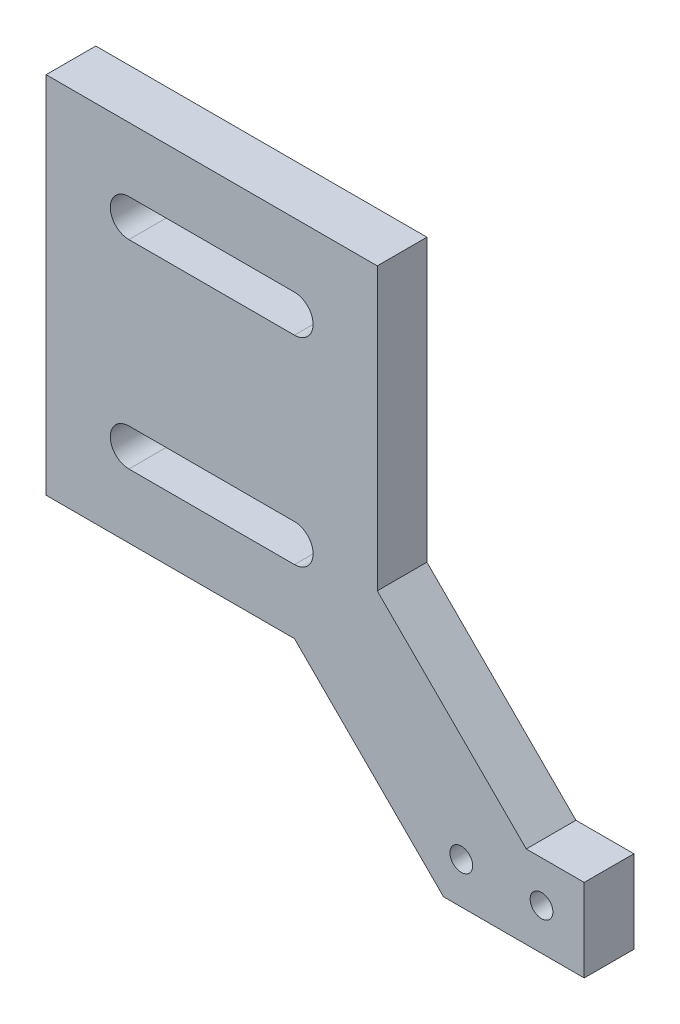
SolidWorks part; units mm, degrees
ref_plane "Front Plane" through (0, 0, 0) normal (0, 0, 1) x (1, 0, 0)
ref_plane "Top Plane" through (0, 0, 0) normal (0, 1, 0) x (1, 0, 0)
ref_plane "Right Plane" through (0, 0, 0) normal (1, 0, 0) x (0, 0, -1)
sketch "Sketch1" plane through (0, 0, 0) normal (0, 0, 1) x (1, 0, 0)
  line L0 (-10, -12) -> (10, -12) construction
  line L1 (20, 22) -> (-20, 22)
  line L2 (20, 22) -> (20, -22)
  line L3 (20, -22) -> (-20, -22)
  line L4 (-20, 22) -> (-20, -22)
  line L5 (20, 22) -> (-20, -22) construction
  line L6 (20, -22) -> (-20, 22) construction
  line L7 (-10, -9.75) -> (10, -9.75)
  line L8 (-10, -14.25) -> (10, -14.25)
  line L9 (-10, 12) -> (10, 12) construction
  line L10 (-10, 14.25) -> (10, 14.25)
  line L11 (-10, 9.75) -> (10, 9.75)
  line L12 (0, 12) -> (0, -12) construction
  arc A0 (-10, -9.75) -> (-10, -14.25) centre (-10, -12) ccw
  arc A1 (10, -14.25) -> (10, -9.75) centre (10, -12) ccw
  arc A2 (-10, 14.25) -> (-10, 9.75) centre (-10, 12) ccw
  arc A3 (10, 9.75) -> (10, 14.25) centre (10, 12) ccw
  point P0 (0, 0)
  point P8 (0, -12)
  point P13 (0, 12)
  dimension "D1" = 20
  dimension "D2" = 24
  dimension "D3" = 10
  dimension "D4" = 4.5
  dimension "D5" = 10
  dimension "D6" = 40
extrude "Boss-Extrude1" add sketch "Sketch1" along normal blind 6
sketch "Sketch2" plane through (0, 0, 0) normal (0, 0, -1) x (-1, 0, 0)
  line L0 (10, -5.75) -> (-10, -5.75)
  line L1 (-10, -18.25) -> (10, -18.25)
  line L2 (10, -9.75) -> (-10, -9.75)
  line L3 (-10, -14.25) -> (10, -14.25)
  line L4 (10, -9.75) -> (-10, -9.75) construction
  line L5 (-10, -14.25) -> (10, -14.25) construction
  line L6 (10, 14.25) -> (-10, 14.25)
  line L7 (-10, 9.75) -> (10, 9.75)
  line L16 (10, 14.25) -> (-10, 14.25) construction
  line L17 (-10, 9.75) -> (10, 9.75) construction
  line L18 (10, 18.25) -> (-10, 18.25)
  line L19 (-10, 5.75) -> (10, 5.75)
  arc A0 (-10, -5.75) -> (-10, -18.25) centre (-10, -12) ccw
  arc A1 (10, -18.25) -> (10, -5.75) centre (10, -12) ccw
  arc A2 (-10, -9.75) -> (-10, -14.25) centre (-10, -12) ccw
  arc A3 (10, -14.25) -> (10, -9.75) centre (10, -12) ccw
  arc A4 (-10, -9.75) -> (-10, -14.25) centre (-10, -12) ccw construction
  arc A5 (10, -14.25) -> (10, -9.75) centre (10, -12) ccw construction
  arc A6 (-10, 14.25) -> (-10, 9.75) centre (-10, 12) ccw
  arc A7 (10, 9.75) -> (10, 14.25) centre (10, 12) ccw
  arc A8 (-10, 14.25) -> (-10, 9.75) centre (-10, 12) ccw construction
  arc A9 (10, 9.75) -> (10, 14.25) centre (10, 12) ccw construction
  arc A10 (-10, 18.25) -> (-10, 5.75) centre (-10, 12) ccw
  arc A11 (10, 5.75) -> (10, 18.25) centre (10, 12) ccw
  dimension "D1" = 0
  dimension "D3" = 0
  dimension "D4" = 4
sketch "Sketch3" plane through (0, 0, 0) normal (0, 0, -1) x (-1, 0, 0)
  line L0 (-20, -12) -> (-38, -30)
  line L1 (-20, -22) -> (-20, 22) construction
  line L2 (-38, -30) -> (-45, -30)
  line L3 (-45, -30) -> (-45, -40)
  line L4 (-45, -40) -> (-28, -40)
  line L6 (-39.845, -35) -> (-30.155, -35) construction
  line L8 (-28, -40) -> (-10, -22)
  line L9 (20, -22) -> (-20, -22) construction
  line L10 (-10, -22) -> (-20, -22)
  line L11 (-20, -22) -> (-20, -12)
  circle A0 centre (-39.845, -35) radius 1.375
  circle A1 centre (-30.155, -35) radius 1.375
  point P11 (-35, -35)
  point P12 (-45, -35)
  dimension "D1" = 9.69
  dimension "D2" = 2.75
  dimension "D3" = 10
  dimension "D4" = 10
  dimension "D5" = 35
  dimension "D6" = 45
  dimension "D7" = 45
  dimension "D8" = 10
  dimension "D9" = 35
  dimension "D10" = 10
extrude "Boss-Extrude2" add sketch "Sketch3" against normal up to surface (6 mm away) up to face at (0, -12, 6)
